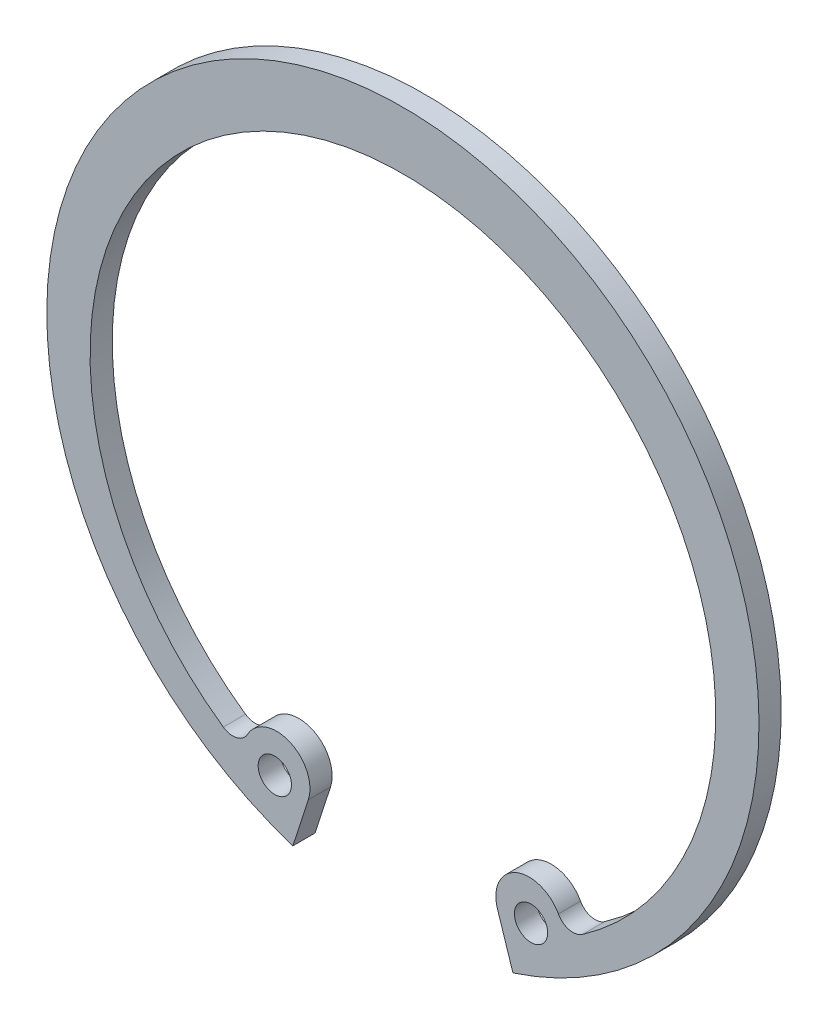
SolidWorks part; units mm, degrees
ref_plane "前视" through (0, 0, 0) normal (0, 0, 1) x (1, 0, 0)
ref_plane "上视" through (0, 0, 0) normal (0, 1, 0) x (1, 0, 0)
ref_plane "右视" through (0, 0, 0) normal (1, 0, 0) x (0, 0, -1)
sketch "尺寸草图" plane through (0, 0, 0) normal (0, 0, 1) x (1, 0, 0)
  line L0 (-32.1, 0) -> (32.1, 0) construction
  line L1 (0, 0) -> (-27.7994, -16.05) construction
  circle A0 centre (0, 0) radius 32.1
  point P5 (-24.3, 0)
  point P6 (26.8, 0)
  point P7 (3, 0)
  point P8 (28.3, 0)
  point P10 (-4.35, 0)
  point P11 (-1.3, 0)
  point P12 (-7.35, 0)
  point P13 (-26.3, 0)
  point P14 (3.3775, 1.95)
  dimension "DD" = 64.2
  dimension "d" = 56.4
  dimension "RR" = 28.3
  dimension "R1" = 3
  dimension "R2" = 1.5
  dimension "aa" = 36
  dimension "a" = 7.35
  dimension "d1" = 3
  dimension "D2" = 30
  dimension "c" = 1.3
  dimension "s" = 2
sketch "草图1" plane through (0, 0, 0) normal (0, 0, 1) x (1, 0, 0)
  line L0 (0, 32.1) -> (0, -30.5289) construction
  line L1 (-8.525, -26.2371) -> (-9.9194, -30.5289)
  line L2 (-11.72, -26.3623) -> (-11.3781, -25.3101) construction
  line L3 (0, 0) -> (-9.9194, -30.5289) construction
  line L4 (8.525, -26.2371) -> (9.9194, -30.5289)
  arc A0 (9.9194, -30.5289) -> (-9.9194, -30.5289) centre (0, 0) ccw
  arc A1 (16.1924, -24.3878) -> (-16.1924, -24.3878) centre (0, -1.3) ccw
  circle A2 centre (-11.5491, -25.8362) radius 1.5
  arc A3 (-8.525, -26.2371) -> (-14.0134, -23.8765) centre (-11.3781, -25.3101) ccw
  arc A4 (-14.0134, -23.8765) -> (-16.1924, -24.3878) centre (-15.3311, -23.1597) cw
  circle A5 centre (11.5491, -25.8362) radius 1.5
  arc A6 (8.525, -26.2371) -> (14.0134, -23.8765) centre (11.3781, -25.3101) cw
  arc A7 (14.0134, -23.8765) -> (16.1924, -24.3878) centre (15.3311, -23.1597) ccw
  dimension "D1" = 64.2
  dimension "D2" = 56.4
  dimension "D5" = 3
  dimension "D7" = 3
  dimension "D8" = 1.5
  dimension "D9" = 7.35
  dimension "D3" = 1.3
  dimension "D4" = 18
  dimension "D6" = 28.3
extrude "基体-拉伸" add sketch "草图1" along normal blind 2
